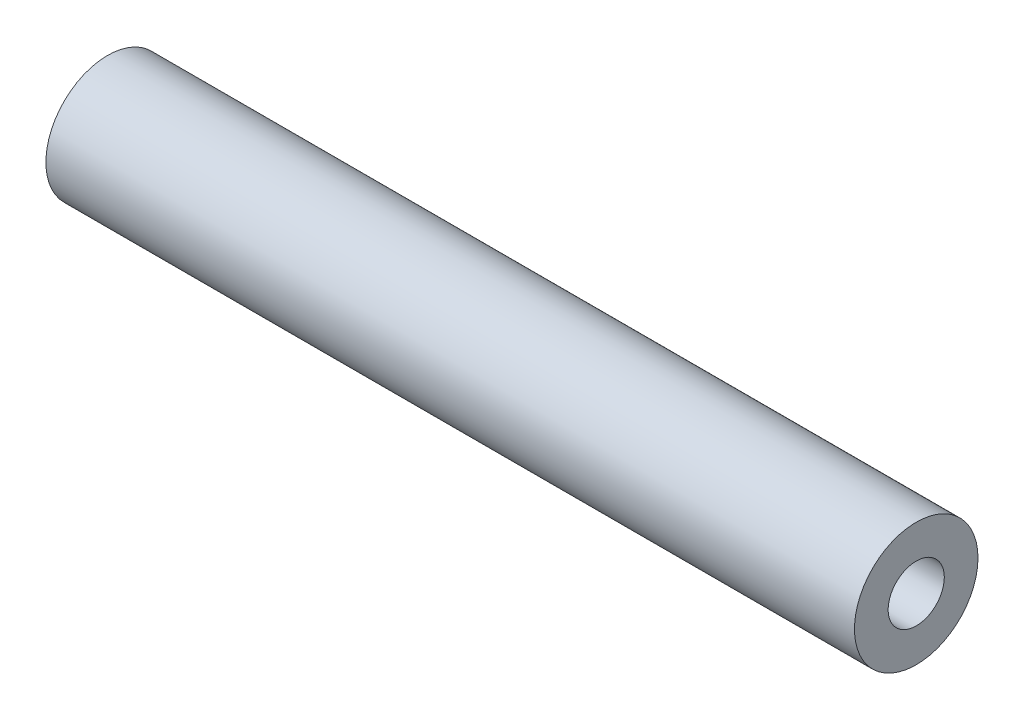
SolidWorks part; units mm, degrees
ref_plane "Front Plane" through (0, 0, 0) normal (0, 0, 1) x (1, 0, 0)
ref_plane "Top Plane" through (0, 0, 0) normal (0, 1, 0) x (1, 0, 0)
ref_plane "Right Plane" through (0, 0, 0) normal (1, 0, 0) x (0, 0, -1)
sketch "Sketch2" plane through (0, 0, 0) normal (1, 0, 0) x (0, 0, -1)
  circle A0 centre (0, 0) radius 1.5875
  circle A1 centre (0, 0) radius 3.4925
  dimension "D1" = 3.175
  dimension "D2" = 6.985
extrude "Boss-Extrude1" add sketch "Sketch2" along normal blind 45.72 contours A1 A0
